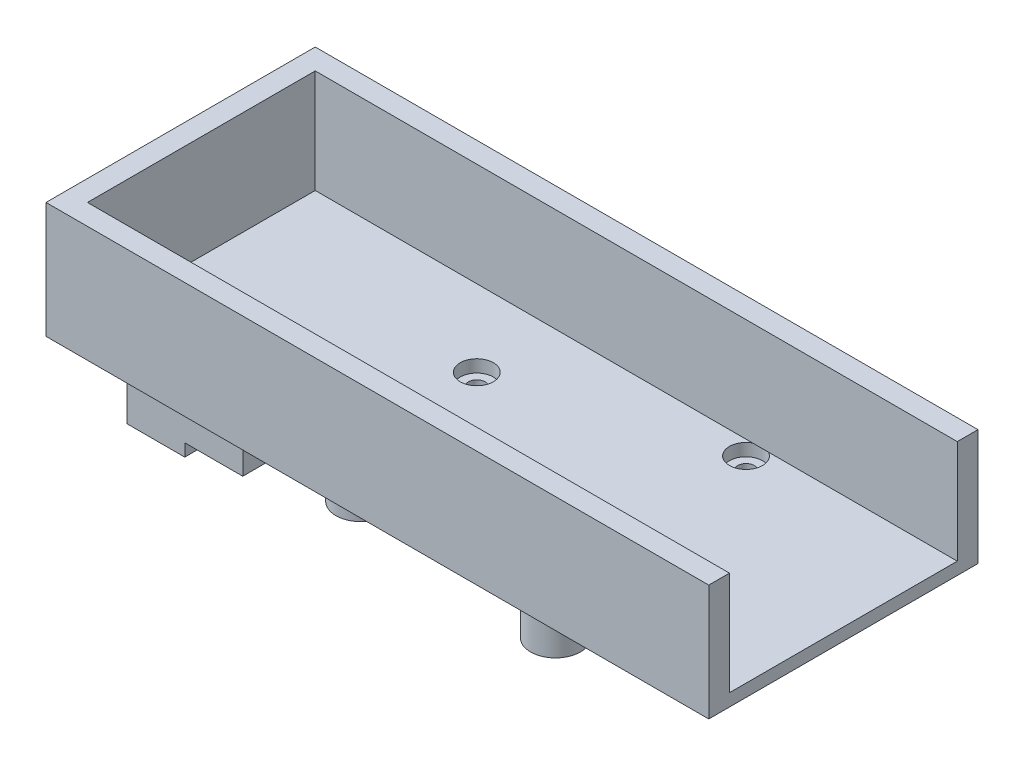
SolidWorks part; units mm, degrees
ref_plane "Front Plane" through (0, 0, 0) normal (0, 0, 1) x (1, 0, 0)
ref_plane "Top Plane" through (0, 0, 0) normal (0, 1, 0) x (1, 0, 0)
ref_plane "Right Plane" through (0, 0, 0) normal (1, 0, 0) x (0, 0, -1)
sketch "Sketch1" plane through (0, 0, 0) normal (0, 1, 0) x (1, 0, 0)
  line L0 (0, 0) -> (52, 0) construction
  line L1 (50, -5) -> (50, 43) construction
  line L2 (0, 0) -> (0, 28) construction
  line L5 (52, 0) -> (52, -5) construction
  line L6 (52, -5) -> (50, -5) construction
  circle A0 centre (0, 28) radius 2
  circle A1 centre (0, 0) radius 2
  circle A4 centre (0, 28) radius 6
  circle A5 centre (0, 0) radius 6
  circle A8 centre (52, -5) radius 2
  circle A9 centre (52, -5) radius 6
  circle A10 centre (50, 43) radius 2
  circle A11 centre (50, 43) radius 6
  dimension "D6" = 4
  dimension "D7" = 12
  dimension "D1" = 52
  dimension "D2" = 48
  dimension "D3" = 28
  dimension "D8" = 5
  dimension "D9" = 2
extrude "Arduino Offset Pins" add sketch "Sketch1" along normal blind 10
sketch "Sketch2" plane through (0, 10, 0) normal (0, 1, 0) x (1, 0, 0)
  line L0 (0, 28) -> (0, 0) construction
  line L5 (-57.5, 46.5) -> (107.5, -8.5) construction
  line L6 (-57.5, -8.5) -> (107.5, 46.5) construction
  line L7 (50, 19) -> (0, 19) construction
  line L8 (50, 43) -> (50, -5) construction
  line L9 (25, 19) -> (25, 27.4992) construction
  line L10 (-62.5, 51.5) -> (97.5, 51.5)
  line L12 (-62.5, -13.5) -> (97.5, -13.5)
  line L13 (-62.5, 51.5) -> (-62.5, -13.5)
  line L14 (97.5, 51.5) -> (97.5, -13.5)
  circle A0 centre (0, 0) radius 2
  circle A1 centre (0, 28) radius 2
  circle A2 centre (50, 43) radius 2
  circle A3 centre (52, -5) radius 2
  point P12 (25, 19)
  dimension "D1" = 55
  dimension "D2" = 165
  dimension "D3" = 160
extrude "battery holder base" add sketch "Sketch2" along normal blind 3
sketch "Sketch3" plane through (0, 13, 0) normal (0, 1, 0) x (1, 0, 0)
  circle A0 centre (0, 0) radius 4
  circle A1 centre (0, 28) radius 4
  circle A2 centre (52, -5) radius 4
  circle A3 centre (50, 43) radius 4
  dimension "D1" = 8
extrude "Battery Holder Arduino Countersink" cut sketch "Sketch3" against normal blind 3
sketch "Sketch4" plane through (0, 13, 0) normal (0, 1, 0) x (1, 0, 0)
  line L1 (-62.5, -13.5) -> (97.5, -13.5)
  line L2 (-62.5, -13.5) -> (-62.5, -8.5)
  line L3 (-62.5, 51.5) -> (97.5, 51.5)
  line L5 (-57.5, 46.5) -> (97.5, 46.5)
  line L7 (-57.5, -8.5) -> (97.5, -8.5)
  line L8 (-57.5, -8.5) -> (107.5, -8.5) construction
  line L9 (-57.5, 46.5) -> (107.5, 46.5) construction
  line L10 (-62.5, 46.5) -> (-62.5, 51.5)
  line L11 (-62.5, -13.5) -> (-62.5, 51.5) construction
  line L12 (-57.5, -8.5) -> (-57.5, 46.5) construction
  line L13 (-62.5, 46.5) -> (-62.5, -8.5)
  line L14 (-57.5, 46.5) -> (-57.5, -8.5)
  line L15 (107.5, -8.5) -> (107.5, 46.5) construction
  line L17 (112.5, -13.5) -> (112.5, 51.5) construction
  line L18 (97.5, 51.5) -> (97.5, 46.5)
  line L19 (97.5, -8.5) -> (97.5, -13.5)
  line L20 (-62.5, 51.5) -> (112.5, 51.5) construction
  line L21 (-62.5, -13.5) -> (112.5, -13.5) construction
  dimension "D2" = 65
  dimension "D3" = 160
  dimension "D1" = 5
  dimension "D4" = 5
extrude "BatteryHolder Walls" add sketch "Sketch4" along normal blind 25
sketch "Sketch6" plane through (0, 10, 0) normal (0, -1, 0) x (1, 0, 0)
  line L3 (-34.5, -32) -> (-34.5, -6)
  line L14 (-37.5, -9) -> (-62.5, -9)
  line L15 (-62.5, -51.5) -> (-62.5, 13.5) construction
  line L16 (-37.5, -19) -> (-62.5, -19) construction
  line L17 (-34.5, -6) -> (-62.5, -6)
  line L18 (-62.5, -6) -> (-62.5, -9)
  line L19 (-62.5, -32) -> (-62.5, -29)
  line L20 (-34.5, -32) -> (-62.5, -32)
  line L21 (-37.5, -29) -> (-62.5, -29)
  line L22 (-43.5, -19) -> (-43.5, -15.6589)
  line L23 (-46.5, -19) -> (-46.5, -15.6589)
  line L24 (-46.5, -15.6589) -> (-43.5, -15.6589)
  line L25 (-46.5, -22.3411) -> (-43.5, -22.3411)
  line L26 (-46.5, -19) -> (-46.5, -22.3411)
  line L27 (-43.5, -19) -> (-43.5, -22.3411)
  line L30 (-37.5, -29) -> (-37.5, -9)
  line L31 (-37.5, -6) -> (-62.5, -6) construction
  dimension "D3" = 3
  dimension "D2" = 10
  dimension "D6" = 3
extrude "SEEED holder walls" add sketch "Sketch6" along normal blind 25
sketch "Sketch7" plane through (0, -15, 0) normal (0, -1, 0) x (1, 0, 0)
  line L0 (-34.5, -6) -> (-48.5, -6) construction
  line L1 (-34.5, -6) -> (-62.5, -6) construction
  line L2 (-48.5, -15.6589) -> (-48.5, -6)
  line L3 (-62.5, -32) -> (-48.5, -32)
  line L4 (-62.5, -32) -> (-62.5, -6)
  line L5 (-62.5, -6) -> (-48.5, -6)
  line L6 (-48.5, -32) -> (-48.5, -22.3411)
  line L7 (-43.5, -15.6589) -> (-48.5, -15.6589)
  line L8 (-43.5, -15.6589) -> (-43.5, -22.3411)
  line L9 (-43.5, -22.3411) -> (-48.5, -22.3411)
  dimension "D1" = 14
extrude "Seeed holder cap" add sketch "Sketch7" along normal blind 3
